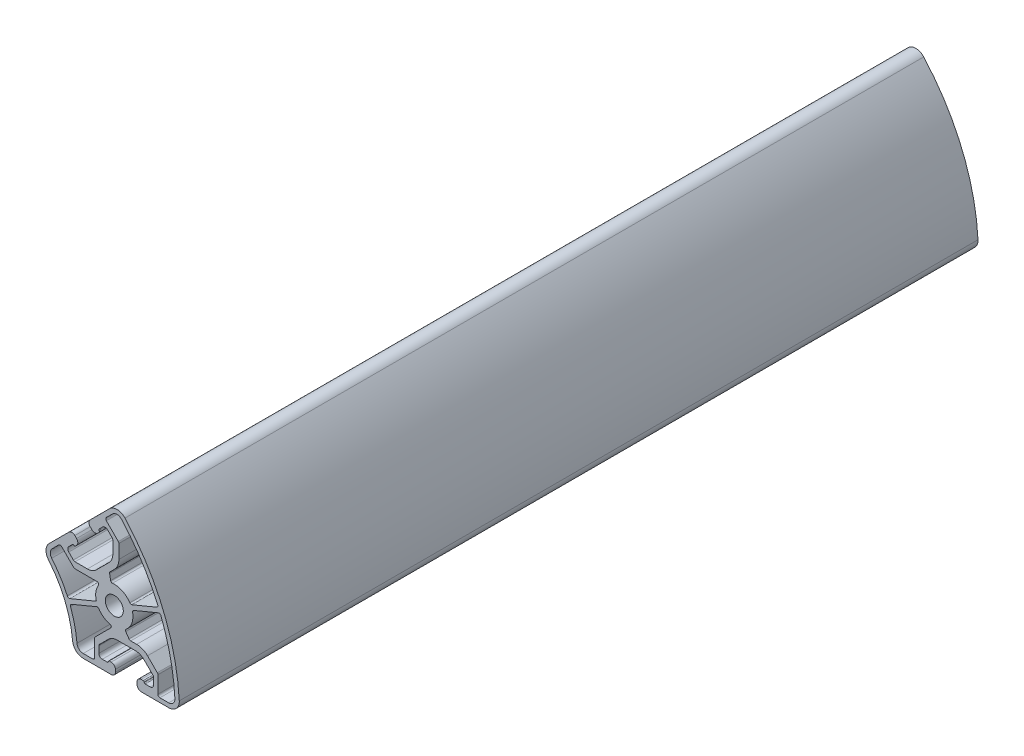
SolidWorks part; units mm, degrees
material "6105-T5 Aluminum"
ref_plane "Front Plane" through (0, 0, 0) normal (0, 0, 1) x (1, 0, 0)
ref_plane "Top Plane" through (0, 0, 0) normal (0, 1, 0) x (1, 0, 0)
ref_plane "Right Plane" through (0, 0, 0) normal (1, 0, 0) x (0, 0, -1)
sketch "Sketch1" plane through (0, 0, 0) normal (0, 0, 1) x (1, 0, 0)
  line L0 (-8.1308, -21.3707) -> (-11.6733, -21.3707)
  line L1 (-16.0216, -7.5293) -> (-6.6079, -3.6301)
  line L2 (-1.3284, -7.8742) -> (-7.1482, -13.694)
  line L3 (-7.3708, -14.2314) -> (-7.3708, -20.6107)
  line L4 (20.4184, -21.3707) -> (17.1382, -21.3707)
  line L5 (16.3782, -20.6107) -> (16.3782, -14.2517)
  line L6 (16.1556, -13.7143) -> (12.486, -10.0448)
  line L7 (8.409, -8.356) -> (6.1544, -8.356)
  line L8 (5.5285, -8.0271) -> (4.3157, -6.2662)
  line L9 (7.2394, 2.1057) -> (16.5084, 5.945)
  line L10 (-19.7876, 9.3638) -> (-15.275, 4.8512)
  line L11 (-14.7376, 4.6286) -> (-6.5073, 4.6286)
  line L12 (-6.7378, -1.8979) -> (-16.6524, -6.0047)
  line L13 (-23.3636, 6.864) -> (-20.8622, 9.3639)
  line L14 (-2.9891, 27.2265) -> (-0.6647, 29.5496)
  line L15 (15.8773, 7.4696) -> (6.6079, 3.6301)
  line L16 (-1.3792, 7.4825) -> (-1.7668, 9.5852)
  line L17 (-1.5568, 10.2604) -> (0.0375, 11.8546)
  line L18 (1.7262, 15.9317) -> (1.7262, 21.1212)
  line L19 (1.5037, 21.6586) -> (-2.9893, 26.1515)
  line L20 (-17.0404, 15.4314) -> (-24.4856, 7.9907)
  line L21 (-11.6705, -22.9607) -> (-1.1445, -22.9607)
  line L22 (0.4301, -21.3861) -> (0.4301, -20.4718)
  line L23 (-1.1445, -18.8972) -> (-1.851, -18.8972)
  line L24 (-2.2307, -19.2639) -> (-2.2317, -19.2924)
  line L25 (-2.6115, -19.6591) -> (-4.5223, -19.6591)
  line L26 (-5.7922, -18.3893) -> (-5.7922, -15.9492)
  line L27 (-5.5318, -15.3207) -> (-2.2454, -12.0343)
  line L28 (1.1128, -10.6433) -> (7.8743, -10.6433)
  line L29 (11.2325, -12.0343) -> (14.5189, -15.3207)
  line L30 (14.7793, -15.9492) -> (14.7793, -18.3893)
  line L31 (13.5094, -19.6591) -> (11.5986, -19.6591)
  line L32 (11.2188, -19.2924) -> (11.2179, -19.2639)
  line L33 (10.8381, -18.8972) -> (10.0682, -18.8972)
  line L34 (8.5571, -20.4629) -> (8.5571, -21.3772)
  line L35 (10.0682, -22.9607) -> (20.4069, -22.9607)
  line L36 (-1.7967, 30.6661) -> (-9.1095, 23.3576)
  line L37 (-9.059, 21.1694) -> (-8.4127, 20.5227)
  line L38 (-6.237, 20.4835) -> (-5.6924, 21.0278)
  line L39 (-5.6831, 21.5555) -> (-5.7025, 21.5764)
  line L40 (-5.6931, 22.1042) -> (-4.3416, 23.455)
  line L41 (-2.5457, 23.4545) -> (-0.8208, 21.7286)
  line L42 (-0.5607, 21.0999) -> (-0.562, 16.4523)
  line L43 (-1.954, 13.0945) -> (-6.7366, 8.3148)
  line L44 (-10.0952, 6.9247) -> (-14.7429, 6.9261)
  line L45 (-15.3713, 7.1867) -> (-17.0962, 8.9126)
  line L46 (-17.0957, 10.7084) -> (-15.7441, 12.0592)
  line L47 (-15.2163, 12.0682) -> (-15.1955, 12.0488)
  line L48 (-14.6677, 12.0578) -> (-14.168, 12.5572)
  line L49 (-14.1673, 14.7841) -> (-14.8136, 15.4308)
  arc A0 (-14.0138, -19.2319) -> (-11.6733, -21.3707) centre (-11.6733, -19.0207) ccw
  arc A1 (-14.0138, -19.2319) -> (-16.4433, -8.4957) centre (-55.4871, -22.9739) ccw
  arc A2 (-16.0216, -7.5293) -> (-16.4433, -8.4957) centre (-15.7307, -8.2315) ccw
  arc A3 (-5.8356, -3.866) -> (-6.6079, -3.6301) centre (-6.3649, -4.2167) ccw
  arc A4 (-5.8356, -3.866) -> (-1.6296, -6.8077) centre (0, 0) ccw
  arc A5 (-1.3284, -7.8742) -> (-1.6296, -6.8077) centre (-1.7774, -7.4252) ccw
  arc A6 (-7.1482, -13.694) -> (-7.3708, -14.2314) centre (-6.6108, -14.2314) ccw
  arc A7 (-8.1308, -21.3707) -> (-7.3708, -20.6107) centre (-8.1308, -20.6107) ccw
  arc A8 (16.3782, -20.6107) -> (17.1382, -21.3707) centre (17.1382, -20.6107) ccw
  arc A9 (16.3782, -14.2517) -> (16.1556, -13.7143) centre (15.6182, -14.2517) ccw
  arc A10 (12.486, -10.0448) -> (8.409, -8.356) centre (8.409, -14.1218) ccw
  arc A11 (5.5285, -8.0271) -> (6.1544, -8.356) centre (6.1544, -7.596) ccw
  arc A12 (4.4362, -5.4148) -> (4.3157, -6.2662) centre (4.8387, -5.906) ccw
  arc A13 (4.4362, -5.4148) -> (6.8601, 1.3927) centre (0, 0) ccw
  arc A14 (7.2394, 2.1057) -> (6.8601, 1.3927) centre (7.4824, 1.519) ccw
  arc A15 (17.5072, 5.5193) -> (16.5084, 5.945) centre (16.7993, 5.2429) ccw
  arc A16 (22.7652, -18.8985) -> (17.5072, 5.5193) centre (-55.4871, -22.9739) ccw
  arc A17 (20.4184, -21.3707) -> (22.7652, -18.8985) centre (20.4184, -19.0207) ccw
  arc A18 (-19.7876, 9.3638) -> (-20.8622, 9.3639) centre (-20.325, 8.8264) ccw
  arc A19 (-15.275, 4.8512) -> (-14.7376, 4.6286) centre (-14.7376, 5.3886) ccw
  arc A20 (-5.966, 3.6615) -> (-6.5073, 4.6286) centre (-6.5073, 3.9936) ccw
  arc A21 (-5.966, 3.6615) -> (-6.7378, -1.8979) centre (0, 0) ccw
  arc A22 (-17.6341, -5.6193) -> (-16.6524, -6.0047) centre (-16.9432, -5.3025) ccw
  arc A23 (-17.6341, -5.6193) -> (-23.5072, 3.6967) centre (-55.4871, -22.9739) ccw
  arc A24 (-23.3636, 6.864) -> (-23.5072, 3.6967) centre (-21.7024, 5.2018) ccw
  arc A25 (-2.9891, 27.2265) -> (-2.9893, 26.1515) centre (-2.4519, 26.6889) ccw
  arc A26 (2.7429, 29.4599) -> (-0.6647, 29.5496) centre (0.9966, 27.8874) ccw
  arc A27 (16.2826, 8.4768) -> (2.7429, 29.4599) centre (-55.4871, -22.9739) ccw
  arc A28 (15.8773, 7.4696) -> (16.2826, 8.4768) centre (15.5865, 8.1717) ccw
  arc A29 (5.8356, 3.866) -> (6.6079, 3.6301) centre (6.3649, 4.2167) ccw
  arc A30 (5.8356, 3.866) -> (-0.692, 6.9657) centre (0, 0) ccw
  arc A31 (-1.3792, 7.4825) -> (-0.692, 6.9657) centre (-0.7547, 7.5976) ccw
  arc A32 (-1.5568, 10.2604) -> (-1.7668, 9.5852) centre (-1.0194, 9.723) ccw
  arc A33 (0.0375, 11.8546) -> (1.7262, 15.9317) centre (-4.0396, 15.9317) ccw
  arc A34 (1.7262, 21.1212) -> (1.5037, 21.6586) centre (0.9662, 21.1212) ccw
  circle A35 centre (0, 0) radius 3.3782
  arc A36 (-24.4856, 7.9907) -> (-24.7333, 2.6036) centre (-21.658, 5.1614) ccw
  arc A37 (-15.6538, -19.3255) -> (-24.7333, 2.6036) centre (-55.4871, -22.9739) ccw
  arc A38 (-15.6538, -19.3255) -> (-11.6705, -22.9607) centre (-11.6705, -18.9607) ccw
  arc A39 (-1.1445, -22.9607) -> (0.4301, -21.3861) centre (-1.1445, -21.3861) ccw
  arc A40 (0.4301, -20.4718) -> (-1.1445, -18.8972) centre (-1.1445, -20.4718) ccw
  arc A41 (-1.851, -18.8972) -> (-2.2307, -19.2639) centre (-1.851, -19.2772) ccw
  arc A42 (-2.6115, -19.6591) -> (-2.2317, -19.2924) centre (-2.6115, -19.2792) ccw
  arc A43 (-5.7922, -18.3893) -> (-4.5223, -19.6591) centre (-4.5223, -18.3893) ccw
  arc A44 (-5.5318, -15.3207) -> (-5.7922, -15.9492) centre (-4.9033, -15.9492) ccw
  arc A45 (1.1128, -10.6433) -> (-2.2454, -12.0343) centre (1.1128, -15.3925) ccw
  arc A46 (11.2325, -12.0343) -> (7.8743, -10.6433) centre (7.8743, -15.3925) ccw
  arc A47 (14.7793, -15.9492) -> (14.5189, -15.3207) centre (13.8904, -15.9492) ccw
  arc A48 (13.5094, -19.6591) -> (14.7793, -18.3893) centre (13.5094, -18.3893) ccw
  arc A49 (11.2188, -19.2924) -> (11.5986, -19.6591) centre (11.5986, -19.2792) ccw
  arc A50 (11.2179, -19.2639) -> (10.8381, -18.8972) centre (10.8381, -19.2772) ccw
  arc A51 (10.0682, -18.8972) -> (8.5571, -20.4629) centre (10.1178, -20.4572) ccw
  arc A52 (8.5571, -21.3772) -> (10.0682, -22.9607) centre (10.1505, -21.3694) ccw
  arc A53 (20.4069, -22.9607) -> (24.4013, -18.7495) centre (20.4069, -18.9607) ccw
  arc A54 (24.4013, -18.7495) -> (4.0055, 30.5111) centre (-55.4871, -22.9739) ccw
  arc A55 (4.0055, 30.5111) -> (-1.7967, 30.6661) centre (1.0309, 27.8368) ccw
  arc A56 (-9.1095, 23.3576) -> (-9.059, 21.1694) centre (-7.9264, 22.2903) ccw
  arc A57 (-8.4127, 20.5227) -> (-6.237, 20.4835) centre (-7.3047, 21.6219) ccw
  arc A58 (-5.6924, 21.0278) -> (-5.6831, 21.5555) centre (-5.961, 21.2965) ccw
  arc A59 (-5.6931, 22.1042) -> (-5.7025, 21.5764) centre (-5.4246, 21.8355) ccw
  arc A60 (-2.5457, 23.4545) -> (-4.3416, 23.455) centre (-3.4439, 22.5568) ccw
  arc A61 (-0.5607, 21.0999) -> (-0.8208, 21.7286) centre (-1.4496, 21.1002) ccw
  arc A62 (-1.954, 13.0945) -> (-0.562, 16.4523) centre (-5.3112, 16.4537) ccw
  arc A63 (-10.0952, 6.9247) -> (-6.7366, 8.3148) centre (-10.0938, 11.674) ccw
  arc A64 (-15.3713, 7.1867) -> (-14.7429, 6.9261) centre (-14.7426, 7.815) ccw
  arc A65 (-17.0957, 10.7084) -> (-17.0962, 8.9126) centre (-16.198, 9.8102) ccw
  arc A66 (-15.2163, 12.0682) -> (-15.7441, 12.0592) centre (-15.4755, 11.7904) ccw
  arc A67 (-15.1955, 12.0488) -> (-14.6677, 12.0578) centre (-14.9362, 12.3266) ccw
  arc A68 (-14.168, 12.5572) -> (-14.1673, 14.7841) centre (-15.281, 13.671) ccw
  arc A69 (-14.8136, 15.4308) -> (-17.0404, 15.4314) centre (-15.9273, 14.3177) ccw
extrude "Extrude1" add sketch "Sketch1" against normal blind 300
